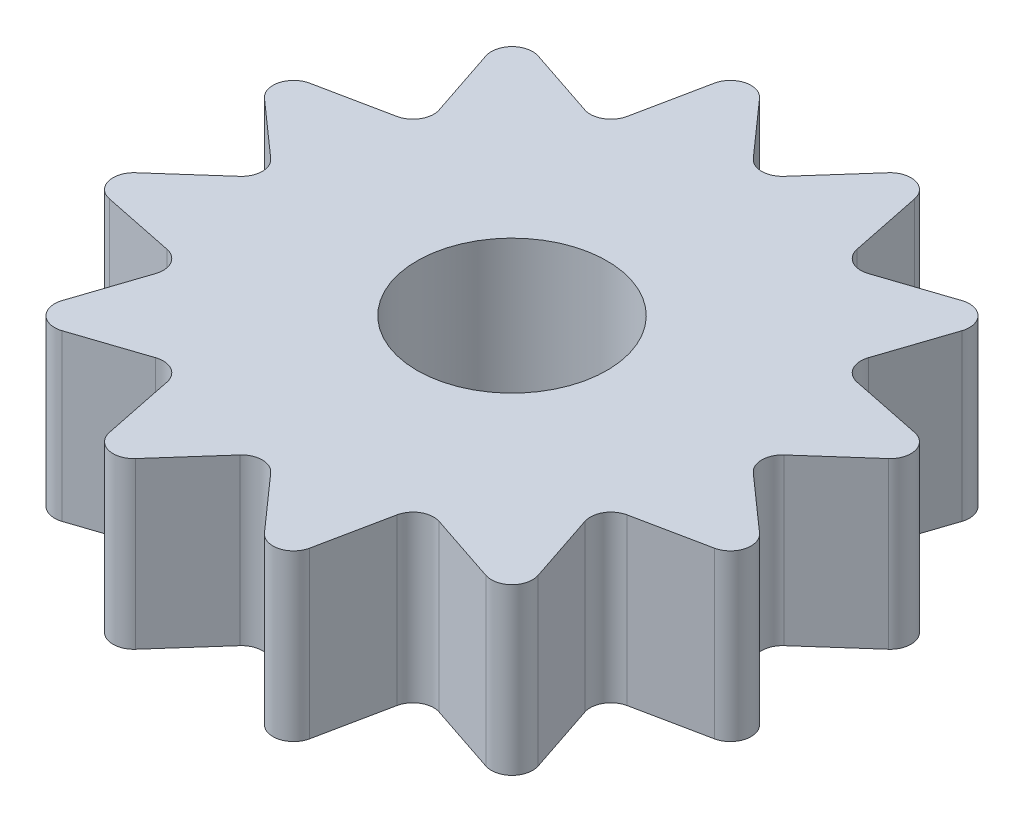
SolidWorks part; units mm, degrees
material "ABS"
ref_plane "Front Plane" through (0, 0, 0) normal (0, 0, 1) x (1, 0, 0)
ref_plane "Top Plane" through (0, 0, 0) normal (0, 1, 0) x (1, 0, 0)
ref_plane "Right Plane" through (0, 0, 0) normal (1, 0, 0) x (0, 0, -1)
sketch "Sketch2" plane through (0, 0, 0) normal (0, 1, 0) x (1, 0, 0)
  line L0 (-2.7847, -5.5715) -> (-2.4258, -7.3254)
  line L9 (0, -5.7956) -> (2.8978, -5.0191)
  line L10 (2.8978, -5.0191) -> (5.0191, -2.8978)
  line L11 (5.0191, -2.8978) -> (5.7956, 0)
  line L12 (5.7956, 0) -> (5.0191, 2.8978)
  line L13 (5.0191, 2.8978) -> (2.8978, 5.0191)
  line L14 (2.8978, 5.0191) -> (0, 5.7956)
  line L15 (0, 5.7956) -> (-2.8978, 5.0191)
  line L16 (-2.8978, 5.0191) -> (-5.0191, 2.8978)
  line L17 (-5.0191, 2.8978) -> (-5.7956, 0)
  line L18 (-5.7956, 0) -> (-5.0191, -2.8978)
  line L19 (-5.0191, -2.8978) -> (-2.8978, -5.0191)
  line L20 (-2.8978, -5.0191) -> (0, -5.7956)
  line L21 (2.4258, -7.3254) -> (2.7847, -5.5715)
  line L22 (0.3741, -6.2174) -> (1.5619, -7.5569)
  line L23 (-1.5619, -7.5569) -> (-0.3741, -6.2174)
  line L24 (-5.1974, -3.4327) -> (-5.7635, -5.1311)
  line L25 (-5.1311, -5.7635) -> (-3.4327, -5.1974)
  line L26 (-6.2174, -0.3741) -> (-7.5569, -1.5619)
  line L27 (-7.3254, -2.4258) -> (-5.5715, -2.7847)
  line L28 (-5.5715, 2.7847) -> (-7.3254, 2.4258)
  line L29 (-7.5569, 1.5619) -> (-6.2174, 0.3741)
  line L30 (-3.4327, 5.1974) -> (-5.1311, 5.7635)
  line L31 (-5.7635, 5.1311) -> (-5.1974, 3.4327)
  line L32 (-0.3741, 6.2174) -> (-1.5619, 7.5569)
  line L33 (-2.4258, 7.3254) -> (-2.7847, 5.5715)
  line L34 (2.7847, 5.5715) -> (2.4258, 7.3254)
  line L35 (1.5619, 7.5569) -> (0.3741, 6.2174)
  line L36 (5.1974, 3.4327) -> (5.7635, 5.1311)
  line L37 (5.1311, 5.7635) -> (3.4327, 5.1974)
  line L38 (6.2174, 0.3741) -> (7.5569, 1.5619)
  line L39 (7.3254, 2.4258) -> (5.5715, 2.7847)
  line L40 (5.5715, -2.7847) -> (7.3254, -2.4258)
  line L41 (7.5569, -1.5619) -> (6.2174, -0.3741)
  line L42 (3.4327, -5.1974) -> (5.1311, -5.7635)
  line L43 (5.7635, -5.1311) -> (5.1974, -3.4327)
  circle A0 centre (0, 0) radius 2.3
  circle A1 centre (0, 0) radius 5.5981 construction
  arc A2 (2.4258, -7.3254) -> (1.5619, -7.5569) centre (1.936, -7.2252) cw
  arc A3 (-1.5619, -7.5569) -> (-2.4258, -7.3254) centre (-1.936, -7.2252) cw
  arc A4 (-5.1311, -5.7635) -> (-5.7635, -5.1311) centre (-5.2892, -5.2892) cw
  arc A5 (-7.3254, -2.4258) -> (-7.5569, -1.5619) centre (-7.2252, -1.936) cw
  arc A6 (-7.5569, 1.5619) -> (-7.3254, 2.4258) centre (-7.2252, 1.936) cw
  arc A7 (-5.7635, 5.1311) -> (-5.1311, 5.7635) centre (-5.2892, 5.2892) cw
  arc A8 (-2.4258, 7.3254) -> (-1.5619, 7.5569) centre (-1.936, 7.2252) cw
  arc A9 (1.5619, 7.5569) -> (2.4258, 7.3254) centre (1.936, 7.2252) cw
  arc A10 (5.1311, 5.7635) -> (5.7635, 5.1311) centre (5.2892, 5.2892) cw
  arc A11 (7.3254, 2.4258) -> (7.5569, 1.5619) centre (7.2252, 1.936) cw
  arc A12 (7.5569, -1.5619) -> (7.3254, -2.4258) centre (7.2252, -1.936) cw
  arc A13 (5.7635, -5.1311) -> (5.1311, -5.7635) centre (5.2892, -5.2892) cw
  arc A14 (2.7847, -5.5715) -> (3.4327, -5.1974) centre (3.2746, -5.6717) cw
  arc A15 (5.1974, -3.4327) -> (5.5715, -2.7847) centre (5.6717, -3.2746) cw
  arc A16 (6.2174, -0.3741) -> (6.2174, 0.3741) centre (6.5492, 0) cw
  arc A17 (5.5715, 2.7847) -> (5.1974, 3.4327) centre (5.6717, 3.2746) cw
  arc A18 (3.4327, 5.1974) -> (2.7847, 5.5715) centre (3.2746, 5.6717) cw
  arc A19 (0.3741, 6.2174) -> (-0.3741, 6.2174) centre (0, 6.5492) cw
  arc A20 (-2.7847, 5.5715) -> (-3.4327, 5.1974) centre (-3.2746, 5.6717) cw
  arc A21 (-5.1974, 3.4327) -> (-5.5715, 2.7847) centre (-5.6717, 3.2746) cw
  arc A22 (-6.2174, 0.3741) -> (-6.2174, -0.3741) centre (-6.5492, 0) cw
  arc A23 (-5.1974, -3.4327) -> (-5.5715, -2.7847) centre (-5.6717, -3.2746) ccw
  arc A24 (-3.4327, -5.1974) -> (-2.7847, -5.5715) centre (-3.2746, -5.6717) cw
  arc A25 (-0.3741, -6.2174) -> (0.3741, -6.2174) centre (0, -6.5492) cw
  point P76 (0, 0)
  dimension "D1" = 0.5
  dimension "D3" = 0.5
  dimension "D2" = 12
extrude "Boss-Extrude1" add sketch "Sketch2" against normal blind 4 contours L19 L20 L9 L10 L11 L12 L13 L14 L15 L16 L17 L18 A0 | A5 L27 L18 L26 | A6 L29 L17 L28 | A7 L31 L16 L30 | A8 L33 L15 L32 | A9 L35 L14 L34 | A10 L37 L13 L36 | A11 L39 L12 L38 | A12 L41 L11 L40 | A13 L43 L10 L42 | A2 L21 L9 L22 | A3 L23 L20 L0 | A4 L25 L19 L24
